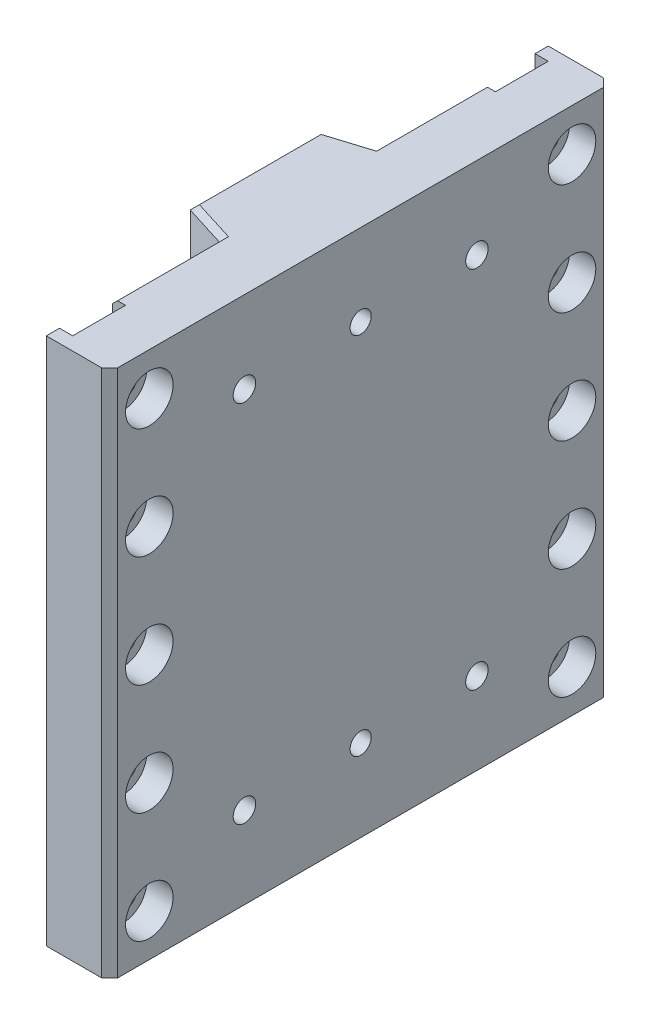
SolidWorks part; units mm, degrees
material "Carburized and nitrided special steel"
ref_plane "Piano frontale" through (0, 0, 0) normal (0, 0, 1) x (1, 0, 0)
ref_plane "Piano superiore" through (0, 0, 0) normal (0, 1, 0) x (1, 0, 0)
ref_plane "Piano destro" through (0, 0, 0) normal (1, 0, 0) x (0, 0, -1)
sketch "Schizzo1" plane through (0, 0, 0) normal (0, 1, 0) x (1, 0, 0)
  line L0 (0, -95) -> (0, 95)
  line L1 (0, 95) -> (-24, 95)
  line L2 (-24, 95) -> (-24, 90)
  line L3 (-24, 90) -> (-19, 90)
  line L4 (-19, 90) -> (-19, 70)
  line L5 (-19, 70) -> (-24, 70)
  line L6 (-24, 70) -> (-24, -70)
  line L7 (0, 0) -> (-73.3731, 0) construction
  line L8 (-19, -70) -> (-24, -70)
  line L9 (-19, -90) -> (-19, -70)
  line L10 (-24, -90) -> (-19, -90)
  line L11 (-24, -95) -> (-24, -90)
  line L12 (0, -95) -> (-24, -95)
  point P11 (-24, 0)
  dimension "D1" = 95
  dimension "D2" = 24
  dimension "D3" = 5
  dimension "D4" = 5
  dimension "D5" = 20
  dimension "D6" = 5
extrude "Estrusione1" add sketch "Schizzo1" along normal blind 200
hole_wizard "M10 Lamatura per vite a copertura cilindrica esagonale2" positions "Schizzo3" profile "Schizzo2" counterbore size "M10" standard "ISO" end condition through all
sketch "Schizzo3" plane through (0, 0, 0) normal (1, 0, 0) x (0, 0, -1)
  line L0 (-95, 200) -> (-95, 0) construction
  line L1 (-95, 200) -> (95, 200) construction
  point P0 (-80, 184)
  dimension "D1" = 15
  dimension "D2" = 16
sketch "Schizzo2" plane through (0, 184, 80) normal (0, 1, 0) x (0, 0, -1)
  line L0 (0, 0) -> (0, 24)
  line L1 (0, 24) -> (5.5, 24)
  line L3 (5.5, 24) -> (5.5, 10)
  line L4 (5.5, 10) -> (9, 10)
  line L5 (9, 10) -> (9, 0)
  line L7 (9, 0) -> (0, 0)
  line L11 (0, -6.35) -> (0, 107.95) construction
  dimension "Thru Hole Dia." = 11
  dimension "Thru Hole Depth" = 24
  dimension "C'Bore Dia." = 18
  dimension "C'Bore Depth" = 10
pattern_linear "Ripetizione a L1" count 5 spacing 42 along (0, -1, 0) count 2 spacing 160 along (0, 0, -1) of "M10 Lamatura per vite a copertura cilindrica esagonale2"
chamfer "Smusso1" distance 3 angle 45 2 edges at (0, 100, -95) (0, 100, 95)
sketch "Schizzo4" plane through (0, 200, 0) normal (0, 1, 0) x (1, 0, 0)
  line L0 (0, 0) -> (-63.6493, 0) construction
  line L1 (0, -92) -> (0, 92) construction
  line L2 (-22, -29.5) -> (-22, 29.5)
  line L3 (-24, 70) -> (-24, -70) construction
  line L4 (-22, 29.5) -> (-31.8247, 29.5)
  line L5 (-31.8247, 29.5) -> (-31.8247, 0)
  line L6 (-22, -29.5) -> (-31.8247, -29.5)
  line L7 (-31.8247, -29.5) -> (-31.8247, 0)
  point P12 (-22, 0)
  dimension "D1" = 29.5
  dimension "D2" = 2
extrude "Estrusione2" cut sketch "Schizzo4" against normal through all
hole_wizard "M10 Lamatura per vite a copertura cilindrica esagonale1" [suppressed] positions "Schizzo6" profile "Schizzo5" counterbore size "M10" standard "ISO"
sketch "Schizzo6" plane through (0, 0, 0) normal (1, 0, 0) x (0, 0, -1)
  line L0 (-92, 0) -> (92, 0) construction
  line L1 (-92, 200) -> (92, 200) construction
  line L2 (-95, 0) -> (-95, 200) construction
  point P0 (0, 150)
  point P1 (0, 50)
  dimension "D1" = 50
  dimension "D2" = 50
  dimension "D3" = 95
  dimension "D4" = 95
sketch "Schizzo5" plane through (0, 150, 0) normal (0, 1, 0) x (0, 0, -1)
  line L0 (0, 0) -> (0, 25)
  line L1 (0, 25) -> (5.5, 25)
  line L3 (5.5, 25) -> (5.5, 10)
  line L4 (5.5, 10) -> (9, 10)
  line L5 (9, 10) -> (9, 0)
  line L7 (9, 0) -> (0, 0)
  line L11 (0, -6.35) -> (0, 107.95) construction
  dimension "Thru Hole Dia." = 11
  dimension "Thru Hole Depth" = 25
  dimension "C'Bore Dia." = 18
  dimension "C'Bore Depth" = 10
hole_wizard "M10 Tapped Hole1" positions "Schizzo9" profile "Schizzo8" tap size "M10" standard "ISO"
sketch "Schizzo9" plane through (0, 0, 0) normal (1, 0, 0) x (0, 0, -1)
  line L0 (-80, 100) -> (92, 100) construction
  line L1 (92, 0) -> (92, 200) construction
  line L2 (0, 0) -> (0, 208.2555) construction
  line L3 (-92, 0) -> (92, 0) construction
  point P0 (-44, 169)
  point P1 (44, 169)
  point P3 (44, 31)
  point P5 (-44, 31)
  dimension "D1" = 44
  dimension "D2" = 44
  dimension "D3" = 44
  dimension "D4" = 44
  dimension "D5" = 69
  dimension "D6" = 69
  dimension "D7" = 69
  dimension "D8" = 69
sketch "Schizzo8" plane through (0, 169, 44) normal (0, 1, 0) x (0, 0, -1)
  line L0 (0, 0) -> (0, 20.0537)
  line L1 (0, 20.0537) -> (4.25, 17.5)
  line L2 (4.25, 17.5) -> (4.25, 0)
  line L5 (4.25, 0) -> (0, 0)
  line L10 (0, 20.0537) -> (-4.25, 17.5) construction
  line L11 (0, -6.35) -> (0, 107.95) construction
  dimension "Tap Drill Dia." = 8.5
  dimension "Tap Drill Depth" = 17.5
  dimension "Drill Angle" = 118
cosmetic thread "Filettatura del foro1" parameters "D1"=10, "D2"=10
cosmetic thread "Filettatura del foro2" parameters "D1"=10, "D2"=10
cosmetic thread "Filettatura del foro3" parameters "D1"=10, "D2"=10
cosmetic thread "Filettatura del foro4" parameters "D1"=10, "D2"=10
sketch "Schizzo10" plane through (0, 0, 0) normal (1, 0, 0) x (0, 0, -1)
  line L0 (0, 0) -> (0, 206.6188) construction
  line L1 (-92, 0) -> (92, 0) construction
  line L2 (-95, 100) -> (112.2303, 100) construction
  line L3 (-95, 0) -> (-95, 200) construction
  circle A0 centre (0, 169) radius 4
  circle A1 centre (0, 31) radius 4
  dimension "D1" = 69
extrude "Estrusione3" cut sketch "Schizzo10" against normal blind 12
sketch "Schizzo11" plane through (0, 200, 0) normal (0, 1, 0) x (1, 0, 0)
  line L0 (-24, 70) -> (-28, 70)
  line L1 (-28, 70) -> (-24, 66)
  line L2 (-24, 70) -> (-24, 29.5) construction
  line L3 (-24, 66) -> (-24, 70)
  line L4 (0, 0) -> (-72.3043, 0) construction
  line L5 (0, -92) -> (0, 92) construction
  line L6 (-24, -66) -> (-24, -70)
  line L7 (-28, -70) -> (-24, -66)
  line L8 (-24, -70) -> (-28, -70)
  dimension "D1" = 4
  dimension "D2" = 135
extrude "Estrusione4" [suppressed] add sketch "Schizzo11" against normal blind 200
sketch "Schizzo12" plane through (0, 200, 0) normal (0, 1, 0) x (1, 0, 0)
  line L0 (-24, 29.5) -> (-40, 24.5)
  line L1 (0, 0) -> (-71.1626, 0) construction
  line L2 (0, -92) -> (0, 92) construction
  line L3 (-40, 24.5) -> (-40, -24.5)
  line L4 (-24, 29.5) -> (-22, 29.5)
  line L5 (-22, 29.5) -> (-22, -29.5)
  line L6 (-22, -29.5) -> (-22, 29.5) construction
  line L7 (-24, -29.5) -> (-22, -29.5)
  line L8 (-24, -29.5) -> (-40, -24.5)
  point P14 (-22, 0)
  point P16 (-40, 0)
  dimension "D1" = 18
  dimension "D2" = 49
extrude "Estrusione5" add sketch "Schizzo12" against normal blind 200
chamfer "Smusso2" distance 2 angle 45 5 edges at (-24, 200, 49.75) (-32, 200, 27) (-40, 200, 0) (-32, 200, -27) (-24, 200, -49.75)
